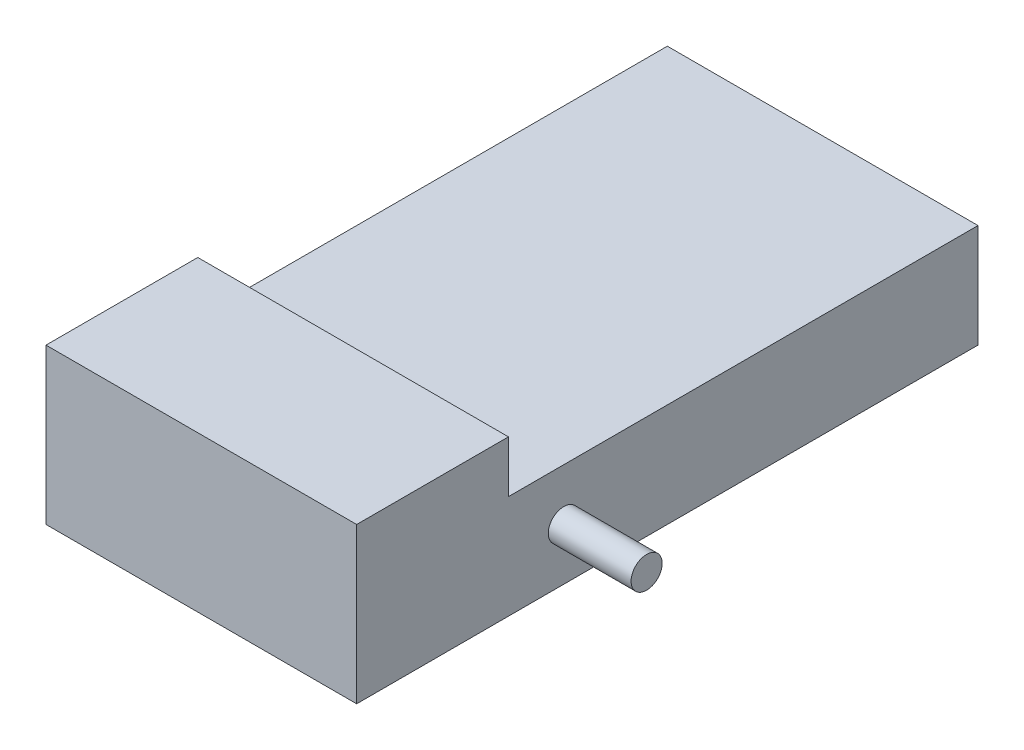
SolidWorks part; units mm, degrees
ref_plane "Front Plane" through (0, 0, 0) normal (0, 0, 1) x (1, 0, 0)
ref_plane "Top Plane" through (0, 0, 0) normal (0, 1, 0) x (1, 0, 0)
ref_plane "Right Plane" through (0, 0, 0) normal (1, 0, 0) x (0, 0, -1)
sketch "Sketch2" plane through (0, 0, 0) normal (0, 1, 0) x (1, 0, 0)
  line L1 (0, 0) -> (38.1, 0)
  line L2 (0, 0) -> (0, 76.2)
  line L3 (0, 76.2) -> (38.1, 76.2)
  line L4 (38.1, 0) -> (38.1, 76.2)
  dimension "D1" = 76.2
  dimension "D2" = 38.1
extrude "Boss-Extrude1" add sketch "Sketch2" along normal blind 12.7
sketch "Sketch3" plane through (0, 0, 0) normal (-1, 0, 0) x (0, 0, 1)
  line L0 (0, 12.7) -> (0, 0) construction
  circle A0 centre (-25.4, 6.4786) radius 1.905
  dimension "D1" = 3.81
  dimension "D2" = 25.4
sketch "Sketch4" plane through (38.1, 0, 0) normal (1, 0, 0) x (0, 0, -1)
  line L0 (0, 12.7) -> (76.2, 12.7) construction
  line L1 (0, 12.7) -> (0, 0) construction
  circle A0 centre (25.4, 6.35) radius 1.905
  dimension "D1" = 3.81
  dimension "D3" = 25.4
  dimension "D2" = 6.35
sketch "Sketch5" plane through (0, 12.7, 0) normal (0, 1, 0) x (1, 0, 0)
  line L0 (38.1, 0) -> (38.1, 76.2) construction
  line L1 (38.1, 18.6147) -> (0, 18.6147)
  line L2 (38.1, 18.6147) -> (38.1, 0)
  line L3 (38.1, 0) -> (0, 0)
  line L4 (0, 18.6147) -> (0, 0)
extrude "Boss-Extrude5" add sketch "Sketch5" along normal blind 2.54
extrude "Boss-Extrude6" add sketch "Sketch4" along normal blind 10.16 contours A0
sketch "Sketch7" plane through (0, 15.24, 0) normal (0, 1, 0) x (1, 0, 0)
  line L1 (38.1, 18.6147) -> (0, 18.6147)
  line L2 (38.1, 18.6147) -> (38.1, 0)
  line L3 (38.1, 0) -> (0, 0)
  line L4 (0, 18.6147) -> (0, 0)
extrude "Boss-Extrude7" add sketch "Sketch7" along normal blind 3.81
